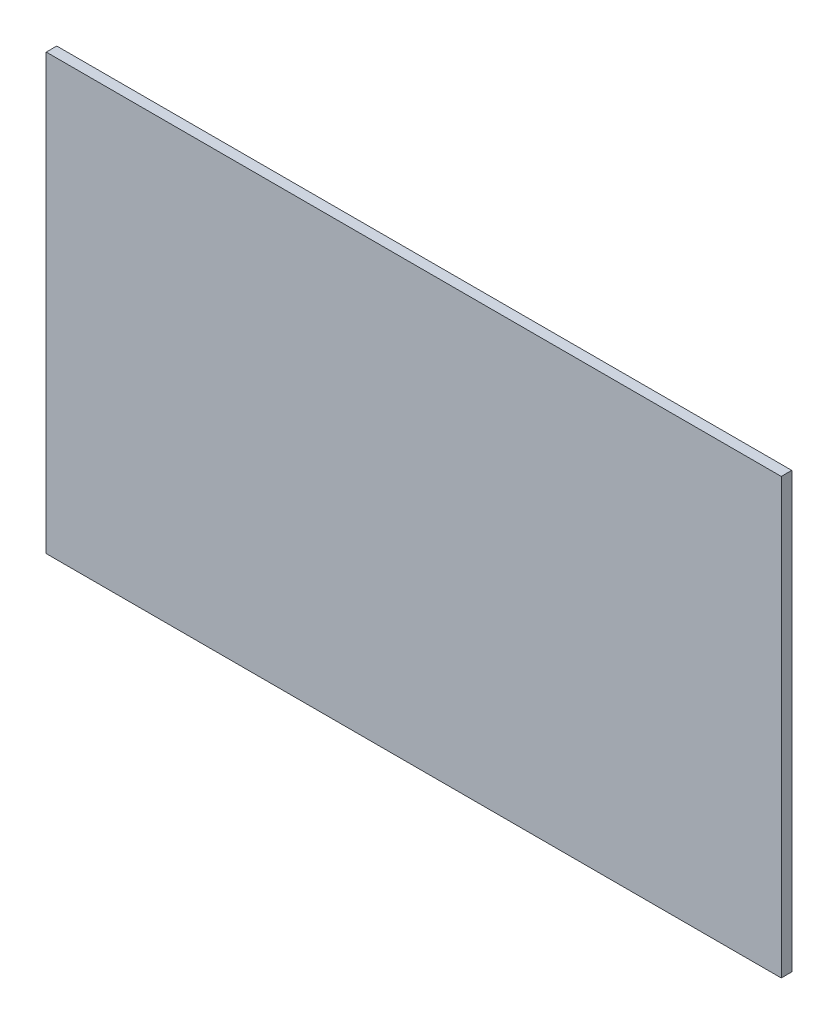
SolidWorks part; units mm, degrees
ref_plane "Front" through (0, 0, 0) normal (0, 0, 1) x (1, 0, 0)
ref_plane "Top" through (0, 0, 0) normal (0, 1, 0) x (1, 0, 0)
ref_plane "Right" through (0, 0, 0) normal (1, 0, 0) x (0, 0, -1)
sketch "Sketch1" plane through (0, 0, 0) normal (0, 0, 1) x (1, 0, 0)
  line L1 (-88.9, 52.5399) -> (88.9, 52.5399)
  line L2 (-88.9, 52.5399) -> (-88.9, -52.5399)
  line L3 (-88.9, -52.5399) -> (88.9, -52.5399)
  line L4 (88.9, 52.5399) -> (88.9, -52.5399)
  line L5 (-88.9, 52.5399) -> (88.9, -52.5399) construction
  line L6 (-88.9, -52.5399) -> (88.9, 52.5399) construction
  point P0 (0, 0)
  dimension "D1" = 177.8
  dimension "D2" = 105.0798
extrude "Boss-Extrude1" add sketch "Sketch1" along normal blind 2.54
